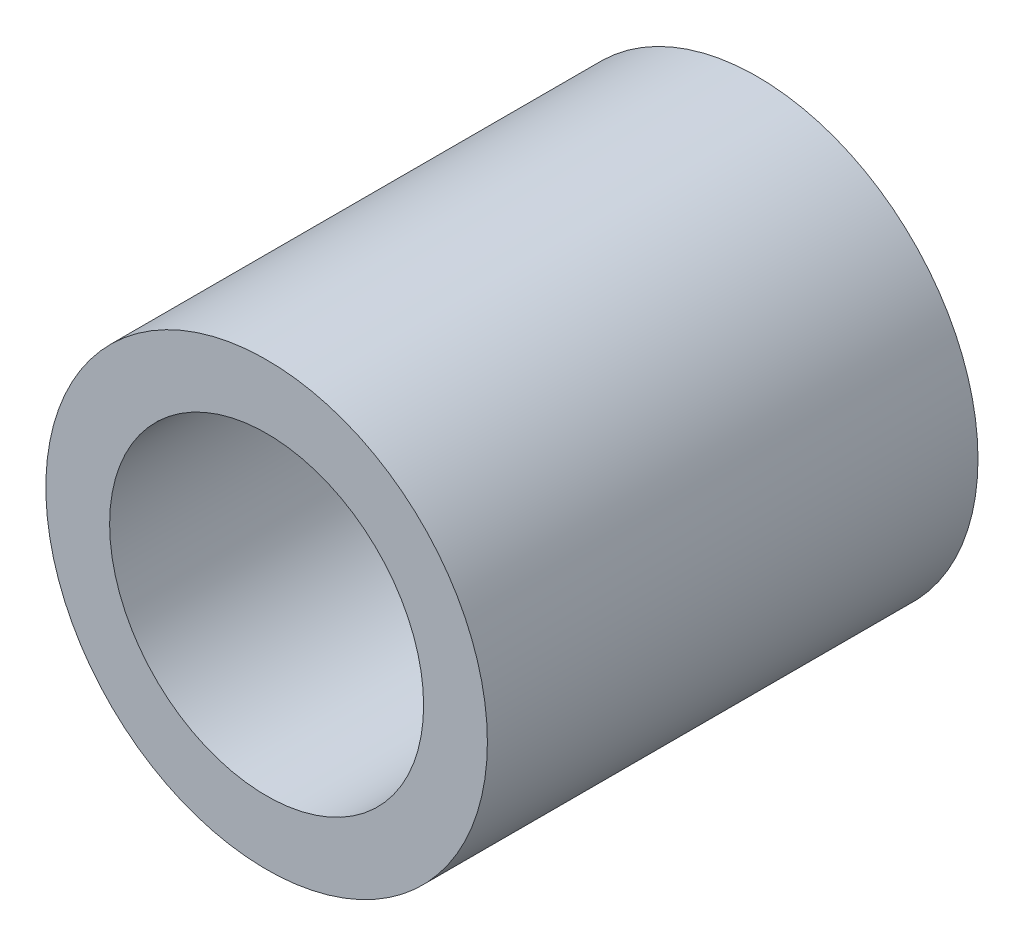
SolidWorks part; units mm, degrees
ref_plane "Front Plane" through (0, 0, 0) normal (0, 0, 1) x (1, 0, 0)
ref_plane "Top Plane" through (0, 0, 0) normal (0, 1, 0) x (1, 0, 0)
ref_plane "Right Plane" through (0, 0, 0) normal (1, 0, 0) x (0, 0, -1)
sketch "Sketch1" plane through (0, 0, 0) normal (0, 0, 1) x (1, 0, 0)
  circle A0 centre (0, 0) radius 2.25
  circle A1 centre (0, 0) radius 1.6
  dimension "OD" = 4.5
  dimension "ID" = 3.2
extrude "Extrude1" add sketch "Sketch1" along normal mid plane 5
sketch "Sketch2" plane through (0, 0, 0) normal (1, 0, 0) x (0, 0, -1)
  line L0 (-2.5, -1.6) -> (2.5, -1.6) construction
  line L3 (2.5, 1.6) -> (-2.5, 1.6) construction
  line L5 (-2.5, -1.6) -> (2.5, -1.6)
  line L6 (2.5, 1.6) -> (-2.5, 1.6)
sketch "Sketch4" plane through (0, 0, 2.5) normal (0, 0, 1) x (1, 0, 0)
  line L0 (0, 0) -> (-1.1314, 1.1314)
  line L1 (0, -1.1) -> (0, 1.1) construction
  circle A0 centre (0, 0) radius 1.6 construction
  dimension "D1" = 45
